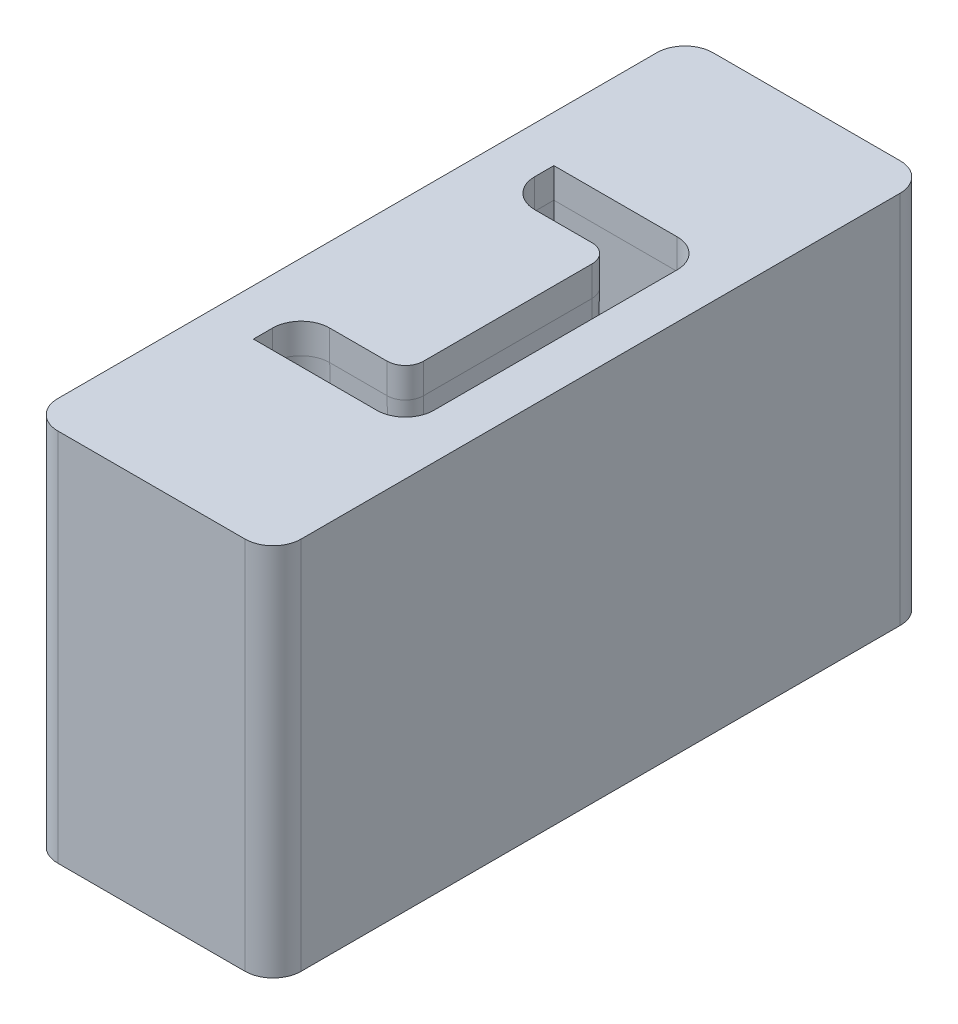
SolidWorks part; units mm, degrees
material "K110"
ref_plane "Front Plane" through (0, 0, 0) normal (0, 0, 1) x (1, 0, 0)
ref_plane "Top Plane" through (0, 0, 0) normal (0, 1, 0) x (1, 0, 0)
ref_plane "Right Plane" through (0, 0, 0) normal (1, 0, 0) x (0, 0, -1)
sketch "Sketch1" plane through (0, 0, 0) normal (0, 1, 0) x (1, 0, 0)
  line L1 (-13, -35) -> (13, -35)
  line L2 (-13, -35) -> (-13, 35)
  line L3 (-13, 35) -> (13, 35)
  line L4 (13, -35) -> (13, 35)
  line L5 (-13, -35) -> (13, 35) construction
  line L6 (-13, 35) -> (13, -35) construction
  point P0 (0, 0)
  dimension "D1" = 70
  dimension "D2" = 26
extrude "Boss-Extrude1" add sketch "Sketch1" against normal blind 40
fillet "Fillet1" radius 3 4 edges at (-13, -20, -35) (13, -20, -35) (-13, -20, 35) (13, -20, 35)
sketch "Sketch9" plane through (0, 0, 0) normal (0, 1, 0) x (1, 0, 0)
  line L72 (3.08, 9) -> (3.08, -9)
  line L73 (1.13, -10.95) -> (-5, -10.95)
  line L74 (-8.05, -14) -> (-8.05, -16.05)
  line L75 (-8.05, -16.05) -> (5.13, -16.05)
  line L76 (8.18, -13) -> (8.18, 13)
  line L77 (5.13, 16.05) -> (-8.05, 16.05)
  line L78 (-8.05, 16.05) -> (-8.05, 14)
  line L79 (-5, 10.95) -> (1.13, 10.95)
  line L80 (3.08, 9) -> (3.08, -9)
  line L81 (1.13, -10.95) -> (-5, -10.95)
  line L82 (-8.05, -14) -> (-8.05, -16.05)
  line L83 (-8.05, -16.05) -> (5.13, -16.05)
  line L84 (8.18, -13) -> (8.18, 13)
  line L85 (5.13, 16.05) -> (-8.05, 16.05)
  line L86 (-8.05, 16.05) -> (-8.05, 14)
  line L87 (-5, 10.95) -> (1.13, 10.95)
  arc A54 (3.08, 9) -> (1.13, 10.95) centre (1.13, 9) ccw
  arc A55 (1.13, -10.95) -> (3.08, -9) centre (1.13, -9) ccw
  arc A56 (-5, -10.95) -> (-8.05, -14) centre (-5, -14) ccw
  arc A57 (5.13, -16.05) -> (8.18, -13) centre (5.13, -13) ccw
  arc A58 (8.18, 13) -> (5.13, 16.05) centre (5.13, 13) ccw
  arc A59 (-8.05, 14) -> (-5, 10.95) centre (-5, 14) ccw
  arc A60 (3.08, 9) -> (1.13, 10.95) centre (1.13, 9) ccw
  arc A61 (1.13, -10.95) -> (3.08, -9) centre (1.13, -9) ccw
  arc A62 (-5, -10.95) -> (-8.05, -14) centre (-5, -14) ccw
  arc A63 (5.13, -16.05) -> (8.18, -13) centre (5.13, -13) ccw
  arc A64 (8.18, 13) -> (5.13, 16.05) centre (5.13, 13) ccw
  arc A65 (-8.05, 14) -> (-5, 10.95) centre (-5, 14) ccw
  dimension "D1" = 0.05
extrude "Cut-Extrude1" cut sketch "Sketch9" against normal up to next
sketch "Sketch11" plane through (0, 0, 0) normal (0, 0, 1) x (1, 0, 0)
  line L0 (8.18, -3.2) -> (8.8223, -40)
  line L2 (-10, -40) -> (10, -40) construction
  line L3 (8.8223, -40) -> (8.18, -40)
  line L4 (8.18, -40) -> (8.18, -3.2)
  line L5 (14.3, 0) -> (-14.3, 0) construction
  line L6 (8.18, -40) -> (8.18, 0) construction
  dimension "D1" = 3.2
  dimension "D2" = 1
sketch "Sketch12" plane through (0, 0, 0) normal (0, 1, 0) x (1, 0, 0)
  line L16 (-8.05, -14) -> (-8.05, -16.05) construction
  line L17 (1.13, -10.95) -> (-5, -10.95) construction
  line L18 (-8.05, 16.05) -> (-8.05, 14) construction
  line L19 (-5, 10.95) -> (1.13, 10.95) construction
  line L20 (3.08, 9) -> (3.08, -9) construction
  line L21 (-8.05, -16.05) -> (5.13, -16.05) construction
  line L22 (8.18, -13) -> (8.18, 13) construction
  line L23 (5.13, 16.05) -> (-8.05, 16.05) construction
  line L24 (-8.05, -14) -> (-8.05, -16.05)
  line L25 (1.13, -10.95) -> (-5, -10.95)
  line L26 (-8.05, 16.05) -> (-8.05, 14)
  line L27 (-5, 10.95) -> (1.13, 10.95)
  line L28 (3.08, 9) -> (3.08, -9)
  line L29 (-8.05, -16.05) -> (5.13, -16.05)
  line L30 (8.18, -13) -> (8.18, 13)
  line L31 (5.13, 16.05) -> (-8.05, 16.05)
  arc A12 (-5, -10.95) -> (-8.05, -14) centre (-5, -14) ccw construction
  arc A13 (1.13, -10.95) -> (3.08, -9) centre (1.13, -9) ccw construction
  arc A14 (-8.05, 14) -> (-5, 10.95) centre (-5, 14) ccw construction
  arc A15 (3.08, 9) -> (1.13, 10.95) centre (1.13, 9) ccw construction
  arc A16 (5.13, -16.05) -> (8.18, -13) centre (5.13, -13) ccw construction
  arc A17 (8.18, 13) -> (5.13, 16.05) centre (5.13, 13) ccw construction
  arc A18 (-5, -10.95) -> (-8.05, -14) centre (-5, -14) ccw
  arc A19 (1.13, -10.95) -> (3.08, -9) centre (1.13, -9) ccw
  arc A20 (-8.05, 14) -> (-5, 10.95) centre (-5, 14) ccw
  arc A21 (3.08, 9) -> (1.13, 10.95) centre (1.13, 9) ccw
  arc A22 (5.13, -16.05) -> (8.18, -13) centre (5.13, -13) ccw
  arc A23 (8.18, 13) -> (5.13, 16.05) centre (5.13, 13) ccw
sweep "Cut-Sweep1" cut profiles "Sketch11" path "Sketch12"
hole_wizard "M8 Tapped Hole1" positions "Sketch16" profile "Sketch14" tap size "M8" standard "ISO"
sketch "Sketch16" plane through (0, -40, 0) normal (0, -1, 0) x (-1, 0, 0)
  line L0 (0, 22) -> (0, -22) construction
  line L2 (0, -35) -> (0, -16.6923) construction
  line L3 (10, -35) -> (-10, -35) construction
  line L5 (0, 35) -> (0, 16.6923) construction
  line L6 (-10, 35) -> (10, 35) construction
  line L10 (8.6923, 16.6923) -> (-5.13, 16.6923) construction
  line L11 (-5.13, -16.6923) -> (8.6923, -16.6923) construction
  point P0 (0, -25.8462)
  point P4 (0, 25.8462)
sketch "Sketch14" plane through (0, -40, 25.8462) normal (1, 0, 0) x (0, 0, -1)
  line L0 (0, 0) -> (0, 24.2929)
  line L1 (0, 24.2929) -> (3.4, 22.25)
  line L2 (3.4, 22.25) -> (3.4, 0)
  line L5 (3.4, 0) -> (0, 0)
  line L10 (0, 24.2929) -> (-3.4, 22.25) construction
  line L11 (0, -6.35) -> (0, 107.95) construction
  dimension "Tap Drill Dia." = 6.8
  dimension "Tap Drill Depth" = 22.25
  dimension "Drill Angle" = 118
cosmetic thread "Hole Thread7"
cosmetic thread "Hole Thread8"
